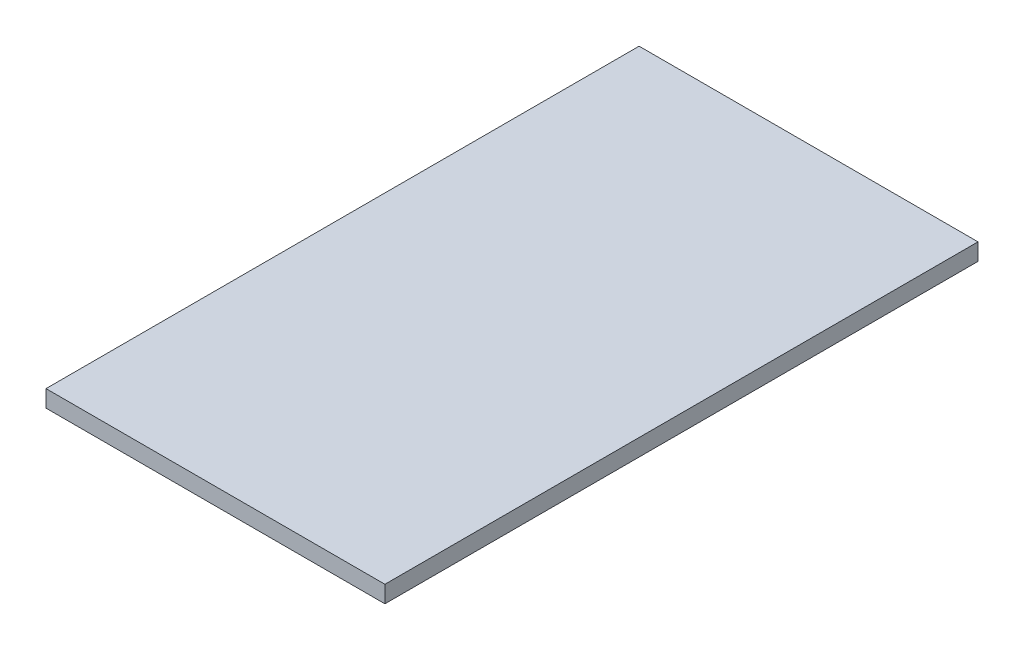
SolidWorks part; units mm, degrees
material "Бук"
ref_plane "Спереди" through (0, 0, 0) normal (0, 0, 1) x (1, 0, 0)
ref_plane "Сверху" through (0, 0, 0) normal (0, 1, 0) x (1, 0, 0)
ref_plane "Справа" through (0, 0, 0) normal (1, 0, 0) x (0, 0, -1)
sketch "Эскиз1" plane through (0, 0, 0) normal (0, 1, 0) x (1, 0, 0)
  line L1 (0, 0) -> (200, 0)
  line L2 (0, 0) -> (0, 350)
  line L3 (0, 350) -> (200, 350)
  line L4 (200, 0) -> (200, 350)
  dimension "D1" = 350
  dimension "D2" = 200
extrude "Бобышка-Вытянуть1" add sketch "Эскиз1" along normal blind 10
